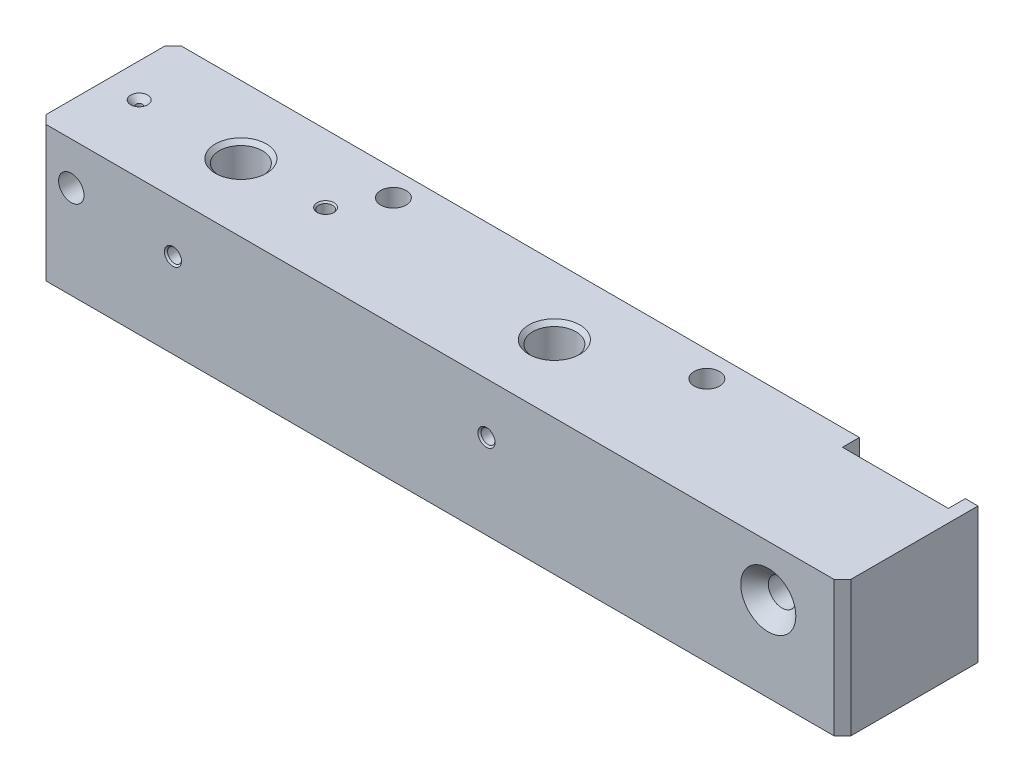
SolidWorks part; units mm, degrees
ref_plane "Front Plane" through (0, 0, 0) normal (0, 0, 1) x (1, 0, 0)
ref_plane "Top Plane" through (0, 0, 0) normal (0, 1, 0) x (1, 0, 0)
ref_plane "Right Plane" through (0, 0, 0) normal (1, 0, 0) x (0, 0, -1)
sketch "Sketch2" plane through (0, 0, 0) normal (0, 0, 1) x (1, 0, 0)
  line L1 (-95, 16) -> (95, 16)
  line L2 (-95, 16) -> (-95, -16)
  line L3 (-95, -16) -> (95, -16)
  line L4 (95, 16) -> (95, -16)
  line L5 (-95, 16) -> (95, -16) construction
  line L6 (-95, -16) -> (95, 16) construction
  point P0 (0, 0)
  dimension "D1" = 190
  dimension "D2" = 32
extrude "Boss-Extrude2" add sketch "Sketch2" along normal mid plane 32
chamfer "Chamfer1" distance 2 angle 45 3 edges at (95, 0, 16) (-95, 0, -16) (-95, 0, 16)
sketch "Sketch3" plane through (0, 16, 0) normal (0, 1, 0) x (1, 0, 0)
  line L0 (95, 16) -> (-93, 16) construction
  line L1 (67, 16) -> (92, 16)
  line L2 (67, 16) -> (67, 12)
  line L3 (67, 12) -> (92, 12)
  line L4 (92, 16) -> (92, 12)
  line L5 (95, -14) -> (95, 16) construction
  dimension "D1" = 25
  dimension "D2" = 4
  dimension "D3" = 3
extrude "Cut-Extrude1" cut sketch "Sketch3" against normal through all
sketch "Sketch4" plane through (0, 16, 0) normal (0, 1, 0) x (1, 0, 0)
  line L0 (-95, 0) -> (95, 0) construction
  line L3 (-95, -14) -> (-95, 14) construction
  line L4 (95, -14) -> (95, 16) construction
  line L5 (11, 16) -> (11, -16) construction
  line L6 (67, 16) -> (-93, 16) construction
  line L7 (93, -16) -> (-93, -16) construction
  line L8 (-63, 16) -> (-63, -16) construction
  line L9 (67, 16) -> (67, 12) construction
  point P17 (67, 14)
  dimension "D1" = 56
  dimension "D2" = 74
hole_wizard "M12 Tapped Hole1" positions "Sketch5" profile "Sketch6" tap size "M12" standard "ISO"
sketch "Sketch5" plane through (0, 16, 0) normal (0, 1, 0) x (1, 0, 0)
  line L0 (-63, 16) -> (-63, -16) construction
  line L1 (11, 16) -> (11, -16) construction
  point P0 (-63, 0)
  point P4 (11, 0)
sketch "Sketch6" plane through (-63, 16, 0) normal (1, 0, 0) x (0, 0, 1)
  line L0 (0, 0) -> (0, 27.0644)
  line L1 (0, 27.0644) -> (5.1, 24)
  line L2 (5.1, 24) -> (5.1, 0.925)
  line L3 (5.1, 0.925) -> (6.025, 0)
  line L5 (6.025, 0) -> (0, 0)
  line L6 (-5.1, 0.925) -> (-6.025, 0) construction
  line L10 (0, 27.0644) -> (-5.1, 24) construction
  line L11 (0, -6.35) -> (0, 107.95) construction
  dimension "Tap Drill Dia." = 10.2
  dimension "Tap Drill Depth" = 24
  dimension "Near C'Sink Dia." = 12.05
  dimension "Near C'Sink Angle" = 90
  dimension "Drill Angle" = 118
cosmetic thread "Hole Thread1" parameters "D1"=24, "D2"=12
cosmetic thread "Hole Thread2" parameters "D1"=24, "D2"=12
sketch "Sketch7" plane through (0, 0, 16) normal (0, 0, 1) x (1, 0, 0)
  line L0 (-63.0616, 16) -> (-63, -8) construction
  line L1 (-95, 16) -> (95, 16) construction
  line L2 (-57.9, -8) -> (-68.1, -8) construction
  line L3 (10.9487, 16) -> (11, -8) construction
  line L4 (16.1, -8) -> (5.9, -8) construction
  line L5 (-63.0308, 4) -> (10.9744, 4) construction
hole_wizard "M4 Tapped Hole1" positions "Sketch8" profile "Sketch9" tap size "M4" standard "ISO"
sketch "Sketch8" plane through (0, 0, 16) normal (0, 0, 1) x (1, 0, 0)
  point P0 (-63.0308, 4)
  point P3 (10.9744, 4)
sketch "Sketch9" plane through (-63.0308, 4, 16) normal (1, 0, 0) x (0, -1, 0)
  line L0 (0, 0) -> (0, 12.4914)
  line L1 (0, 12.4914) -> (1.65, 11.5)
  line L2 (1.65, 11.5) -> (1.65, 0.375)
  line L3 (1.65, 0.375) -> (2.025, 0)
  line L5 (2.025, 0) -> (0, 0)
  line L6 (-1.65, 0.375) -> (-2.025, 0) construction
  line L10 (0, 12.4914) -> (-1.65, 11.5) construction
  line L11 (0, -6.35) -> (0, 107.95) construction
  dimension "Tap Drill Dia." = 3.3
  dimension "Tap Drill Depth" = 11.5
  dimension "Near C'Sink Dia." = 4.05
  dimension "Near C'Sink Angle" = 90
  dimension "Drill Angle" = 118
cosmetic thread "Hole Thread3" parameters "D1"=8, "D2"=4
cosmetic thread "Hole Thread4" parameters "D1"=8, "D2"=4
sketch "Sketch10" plane through (0, 0, 16) normal (0, 0, 1) x (1, 0, 0)
  line L0 (77.5, -16) -> (77.5, 4) construction
  line L1 (-93, -16) -> (93, -16) construction
  line L2 (77.5, 4) -> (93, 4) construction
  line L3 (93, -16) -> (93, 16) construction
  dimension "D1" = 15.5
  dimension "D2" = 20
hole_wizard "CSK for M10 Countersunk Flat Head Screw1" positions "Sketch11" profile "Sketch12" countersink size "M10" standard "ISO" end condition through all
sketch "Sketch11" plane through (0, 0, 16) normal (0, 0, 1) x (1, 0, 0)
  point P0 (77.5, 4)
sketch "Sketch12" plane through (77.5, 4, 16) normal (1, 0, 0) x (0, -1, 0)
  line L0 (0, 0) -> (0, 32)
  line L1 (0, 32) -> (3.25, 32)
  line L2 (3.25, 32) -> (3.25, 3.25)
  line L3 (3.25, 3.25) -> (6.5, 0)
  line L5 (6.5, 0) -> (0, 0)
  line L6 (-3.25, 3.25) -> (-6.5, 0) construction
  line L11 (0, -6.35) -> (0, 107.95) construction
  dimension "Thru Hole Dia." = 6.5
  dimension "Thru Hole Depth" = 32
  dimension "Near C'Sink Dia." = 13
  dimension "Near C'Sink Angle" = 90
sketch "Sketch13" plane through (0, 0, 16) normal (0, 0, 1) x (1, 0, 0)
  line L0 (-63.0308, 4) -> (-87.0308, 4) construction
  line L1 (-63.0616, 16) -> (-63, -8) construction
  line L2 (-87.0308, 4) -> (-87.0308, 18.2215) construction
  line L3 (-93, -16) -> (93, -16) construction
  circle A0 centre (-87.0308, 6) radius 3
  dimension "D1" = 22
  dimension "D3" = 6
  dimension "D2" = 24
extrude "Cut-Extrude2" cut sketch "Sketch13" against normal through all
hole_wizard "CSK for M4 Countersunk Flat Head Screw1" positions "Sketch14" profile "Sketch15" countersink size "M4" standard "ISO"
sketch "Sketch14" plane through (0, 16, 0) normal (0, 1, 0) x (1, 0, 0)
  line L0 (-95, 0) -> (95, 0) construction
  point P0 (-87, 0)
  dimension "D1" = 24
sketch "Sketch15" plane through (-87, 16, 0) normal (1, 0, 0) x (0, 0, 1)
  line L0 (0, 0) -> (0, 10.4506)
  line L1 (0, 10.4506) -> (0.75, 10)
  line L2 (0.75, 10) -> (0.75, 1.25)
  line L3 (0.75, 1.25) -> (2, 0)
  line L5 (2, 0) -> (0, 0)
  line L6 (-0.75, 1.25) -> (-2, 0) construction
  line L10 (0, 10.4506) -> (-0.75, 10) construction
  line L11 (0, -6.35) -> (0, 107.95) construction
  dimension "Hole Dia." = 1.5
  dimension "Hole Depth" = 10
  dimension "Near C'Sink Dia." = 4
  dimension "Near C'Sink Angle" = 90
  dimension "Drill Angle" = 118
hole_wizard "M4 Tapped Hole2" positions "Sketch17" profile "Sketch18" tap size "M4" standard "ISO"
sketch "Sketch17" plane through (0, 16, 0) normal (0, 1, 0) x (1, 0, 0)
  line L0 (-95, 0) -> (95, 0) construction
  point P0 (-43, 0)
  dimension "D1" = 20
sketch "Sketch18" plane through (-43, 16, 0) normal (1, 0, 0) x (0, 0, 1)
  line L0 (0, 0) -> (0, 16.9914)
  line L1 (0, 16.9914) -> (1.65, 16)
  line L2 (1.65, 16) -> (1.65, 0.35)
  line L3 (1.65, 0.35) -> (2, 0)
  line L5 (2, 0) -> (0, 0)
  line L6 (-1.65, 0.35) -> (-2, 0) construction
  line L10 (0, 16.9914) -> (-1.65, 16) construction
  line L11 (0, -6.35) -> (0, 107.95) construction
  dimension "Tap Drill Dia." = 3.3
  dimension "Tap Drill Depth" = 16
  dimension "Near C'Sink Dia." = 4
  dimension "Near C'Sink Angle" = 90
  dimension "Drill Angle" = 118
cosmetic thread "Hole Thread5" parameters "D1"=8, "D2"=4
sketch "Sketch19" plane through (0, 16, 0) normal (0, 1, 0) x (1, 0, 0)
  line L1 (67, 16) -> (-93, 16) construction
  line L2 (-95, -14) -> (-95, 14) construction
  circle A0 centre (-37, 10) radius 3
  circle A1 centre (37, 10) radius 3
  dimension "D1" = 74
  dimension "D4" = 6
  dimension "D2" = 6
  dimension "D3" = 58
extrude "Cut-Extrude3" cut sketch "Sketch19" against normal through all
